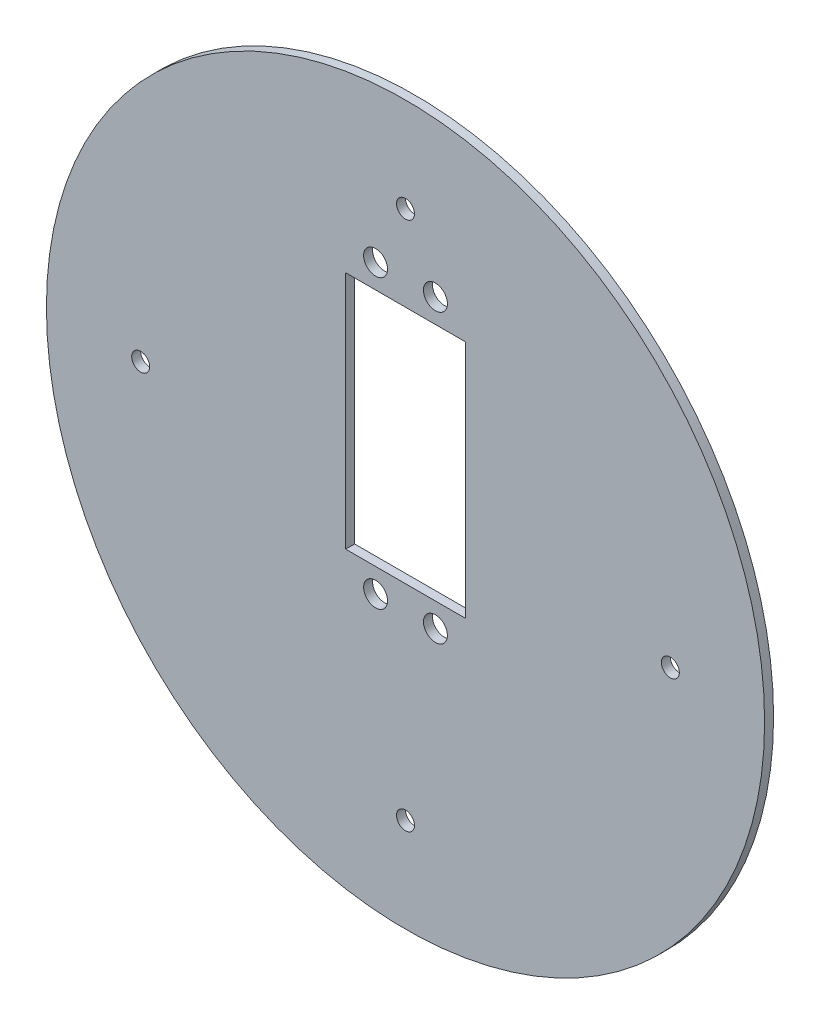
SolidWorks part; units mm, degrees
ref_plane "前视基准面" through (0, 0, 0) normal (0, 0, 1) x (1, 0, 0)
ref_plane "上视基准面" through (0, 0, 0) normal (0, 1, 0) x (1, 0, 0)
ref_plane "右视基准面" through (0, 0, 0) normal (1, 0, 0) x (0, 0, -1)
sketch "草图1" plane through (0, 0, 0) normal (0, 0, 1) x (1, 0, 0)
  line L0 (-10, 30) -> (10, 30)
  line L2 (10, 30) -> (10, -10)
  line L3 (10, -10) -> (-10, -10)
  line L4 (-10, -10) -> (-10, 30)
  circle A0 centre (0, 0) radius 60
  circle A1 centre (5, 34) radius 2
  circle A2 centre (-5, 34) radius 2
  circle A3 centre (5, -14) radius 2
  circle A4 centre (-5, -14) radius 2
  circle A5 centre (0, 44.25) radius 1.5
  circle A6 centre (44.25, 0) radius 1.5
  circle A7 centre (0, -44.25) radius 1.5
  circle A8 centre (-44.25, 0) radius 1.5
  point P27 (0, 0)
  dimension "D1" = 4
extrude "凸台-拉伸1" add sketch "草图1" along normal blind 1.5
